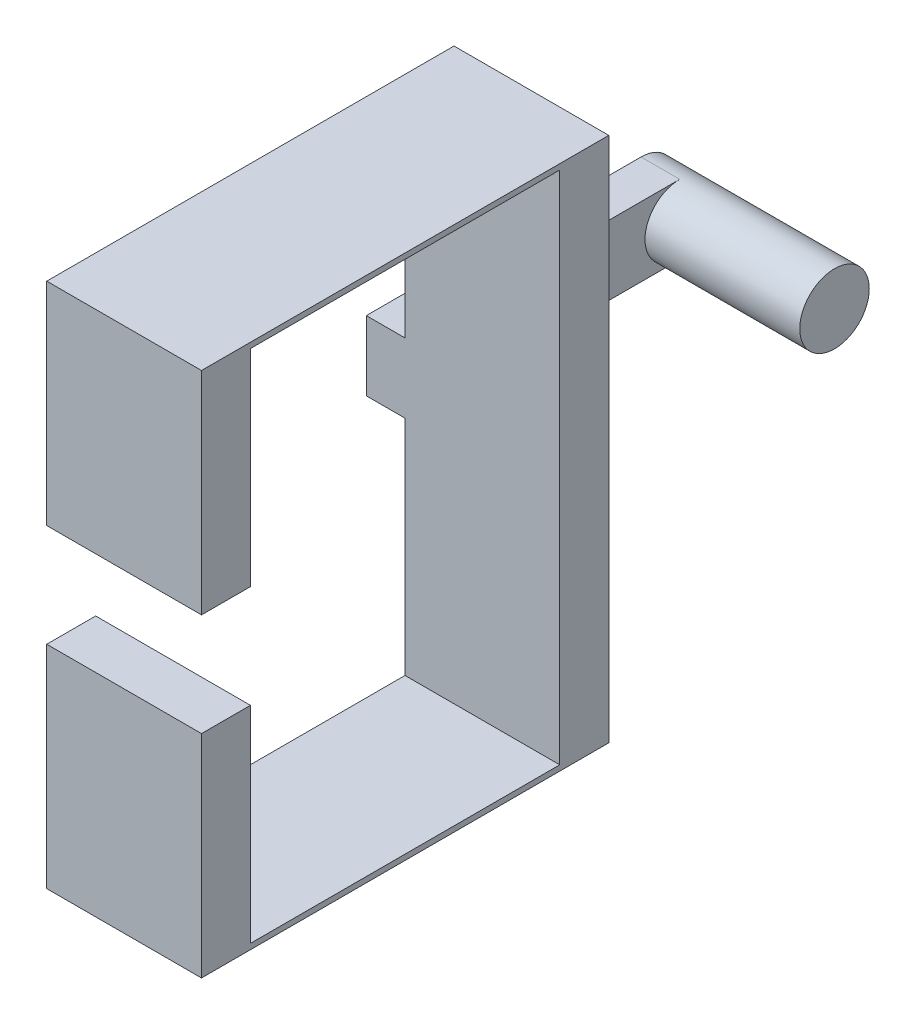
SolidWorks part; units mm, degrees
material "Ti-6Al-4VSolution treated and aged (SS)"
ref_plane "Front Plane" through (0, 0, 0) normal (1, 0, 0) x (0, 1, 0)
ref_plane "Top Plane" through (0, 0, 0) normal (0, 0, 1) x (0, 1, 0)
ref_plane "Right Plane" through (0, 0, 0) normal (0, 1, 0) x (-1, 0, 0)
sketch "Sketch1" plane through (0, 0, 0) normal (1, 0, 0) x (0, 1, 0)
  line L0 (0, 0) -> (0, 50.1335)
  line L1 (0, 50.1335) -> (26.057, 50.1335)
  line L2 (26.057, 50.1335) -> (26.057, 44.1106)
  line L3 (26.057, 44.1106) -> (0.6773, 44.1106)
  line L4 (0.6773, 44.1106) -> (0.6773, 6.036)
  line L5 (0.6773, 6.036) -> (64.0859, 6.036)
  line L6 (0, 0) -> (64.7632, 0)
  line L7 (32.3816, 0) -> (32.3816, 6.036) construction
  line L8 (32.3816, 6.036) -> (32.3816, 65.3702) construction
  line L9 (64.0859, 44.1106) -> (64.0859, 6.036)
  line L10 (38.7062, 44.1106) -> (64.0859, 44.1106)
  line L11 (38.7062, 50.1335) -> (38.7062, 44.1106)
  line L12 (64.7632, 50.1335) -> (38.7062, 50.1335)
  line L13 (64.7632, 0) -> (64.7632, 50.1335)
  dimension "D1" = 38.0746
  dimension "D2" = 6.036
  dimension "D3" = 6.023
  dimension "D4" = 0.6773
  dimension "D5" = 64.7632
  dimension "D6" = 25.3797
extrude "Boss-Extrude1" add sketch "Sketch1" along normal blind 19.05
sketch "Sketch2" plane through (0, 0, 0) normal (-1, 0, 0) x (0, -1, 0)
  line L0 (-32.3816, 0) -> (-32.3816, 50.587) construction
  line L1 (0, 0) -> (-64.7632, 0) construction
  line L2 (-64.0859, 6.036) -> (-0.6773, 6.036) construction
  line L3 (-36.6587, 6.036) -> (-28.1045, 6.036)
  line L4 (-36.6587, 6.036) -> (-36.6587, -32.064)
  line L5 (-36.6587, -32.064) -> (-28.1045, -32.064)
  line L6 (-28.1045, 6.036) -> (-28.1045, -32.064)
  point P10 (-32.3816, 6.036)
  dimension "D1" = 8.5542
  dimension "D2" = 38.1
extrude "Boss-Extrude2" add sketch "Sketch2" along normal blind 4.7634
sketch "Sketch3" plane through (0, 0, 0) normal (1, 0, 0) x (0, 1, 0)
  line L0 (28.1045, -32.064) -> (28.1045, 0) construction
  line L3 (36.6587, 0) -> (36.6587, -32.064) construction
  line L4 (36.6587, -32.064) -> (28.1045, -32.064) construction
  circle A0 centre (32.3816, -27.7869) radius 4.2771
extrude "Boss-Extrude3" add sketch "Sketch3" along normal blind 19.05
sketch "Sketch5" plane through (0, 0, 0) normal (1, 0, 0) x (0, 1, 0)
  line L0 (32.3816, -32.064) -> (36.6587, -32.064)
  line L1 (36.6587, -32.064) -> (36.6587, -27.7869)
  arc A0 (32.3816, -32.064) -> (36.6587, -27.7869) centre (32.3816, -27.7869) ccw
extrude "Cut-Extrude1" cut sketch "Sketch5" against normal up to next
sketch "Sketch6" plane through (0, 0, 0) normal (1, 0, 0) x (0, 1, 0)
  line L0 (28.1045, -27.7869) -> (28.1045, -32.064)
  line L1 (28.1045, -32.064) -> (32.3816, -32.064)
  arc A0 (28.1045, -27.7869) -> (32.3816, -32.064) centre (32.3816, -27.7869) ccw
extrude "Cut-Extrude2" cut sketch "Sketch6" against normal up to next
equation "\"a\"= 0.498in"
equation "\"b\"= 0.9992in"
equation "\"c\"= 1.499in"
equation "\"gamma\"= 0.005in"
equation "\"F\"= 600"
equation "\"SF\"= 4"
equation "\"Emod\"= 15199999.87"
equation "\"TenStr\"= 152289.6245"
equation "\"YieldStr\"= 120000.0006"
equation "\"MaxStress\"= \"YieldStr\" / \"SF\""
equation "\"CylLen\"= .75"
equation "\"rCyl\"= ( ( \"F\" * \"CylLen\" * \"SF\" ) / ( pi * \"YieldStr\" ) ) ^ ( 1 / 3 )"
equation "\"dCyl\"= 2 * \"rCyl\""
equation "\"dLink\"= 1.00"
equation "\"xLink\"= 0.05"
equation "\"yLink\"= 0.04"
equation "\"rLink\"= ( \"dLink\" / 2 ) + \"xLink\""
equation "\"widthLink\"= \"rLink\" * 2"
equation "\"LBar\"= 2 * \"rLink\""
equation "\"wBar\"= ( 2 * \"F\" * \"SF\" ) / ( ( 2 * \"rCyl\" ) * \"Emod\" * \"gamma\" )"
equation "\"Feat1Z\"= ( \"F\" * \"SF\" ) / ( \"YieldStr\" * \"CylLen\" )"
equation "\"Feat2Z\"= ( \"SF\" * \"F\" ) / ( \"YieldStr\" * \"CylLen\" )"
equation "\"Feat3Z\"= ( \"F\" * \"SF\" ) / ( \"CylLen\" * \"YieldStr\" )"
equation "\"hFeat1\"= ( ( \"F\" * \"SF\" * ( \"CylLen\" ) ^ 3 ) / ( \"b\" * \"Emod\" * \"gamma\" ) ) ^ ( 1 / 3 )"
equation "\"wFeat3\"= 2 * \"b\" + 2 * \"Feat1Z\" + \"a\""
equation "\"hFeat3\"= ( ( 6 * \"F\" * ( 0.5 * \"wFeat3\" ) ) / ( \"CylLen\" * \"Emod\" ) ) ^ ( 1 / 2 )"
equation "\"hStiffFeat3\"= ( ( \"F\" * ( 0.5 * \"wFeat3\" ) ) / ( \"CylLen\" * \"Emod\" * \"gamma\" ) ) ^ ( 1 / 3 )"
equation "\"D1@Sketch1\"=\"c\""
equation "\"D2@Sketch1\"=\"hStiffFeat3\""
equation "\"D3@Sketch1\"=\"hFeat1\""
equation "\"D4@Sketch1\"=\"Feat1Z\""
equation "\"D5@Sketch1\"=\"wFeat3\""
equation "\"D1@Boss-Extrude1\"=\"CylLen\""
equation "\"D1@Sketch2\"=\"dCyl\""
equation "\"D2@Sketch2\"=1.5*\"dLink\""
equation "\"D1@Boss-Extrude2\"=\"wBar\""
equation "\"D1@Boss-Extrude3\"=\"CylLen\""
equation "\"D6@Sketch1\"=\"b\""
